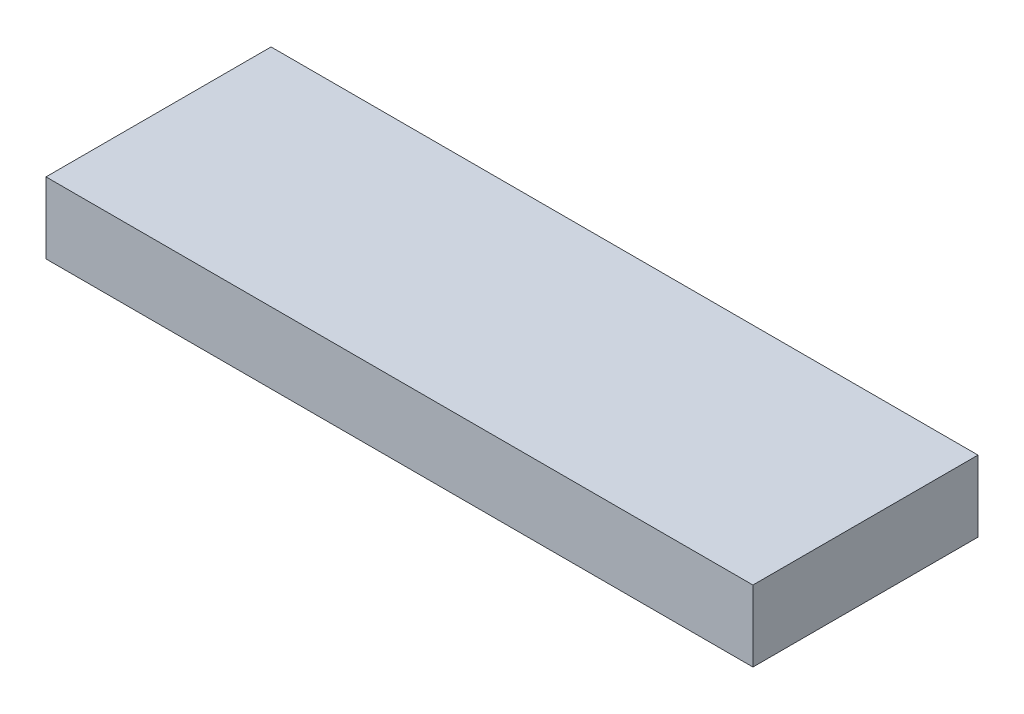
SolidWorks part; units mm, degrees
material "MDF"
ref_plane "Front Plane" through (0, 0, 0) normal (0, 0, 1) x (1, 0, 0)
ref_plane "Top Plane" through (0, 0, 0) normal (0, 1, 0) x (1, 0, 0)
ref_plane "Right Plane" through (0, 0, 0) normal (1, 0, 0) x (0, 0, -1)
sketch "Sketch1" plane through (0, 0, 0) normal (0, 0, 1) x (1, 0, 0)
  line L1 (133.8612, 0) -> (323.3388, 0)
  line L2 (133.8612, 0) -> (133.8612, -19.05)
  line L3 (133.8612, -19.05) -> (323.3388, -19.05)
  line L4 (323.3388, 0) -> (323.3388, -19.05)
  line L5 (323.3388, -298.45) -> (323.3388, 20.8246) construction
  line L6 (133.8612, -298.45) -> (133.8612, 20.8246) construction
  line L8 (456.6888, 0) -> (0.5112, 0) construction
  dimension "D1" = 19.05
extrude "Boss-Extrude1" add sketch "Sketch1" along normal up to surface (60.325 mm away)
